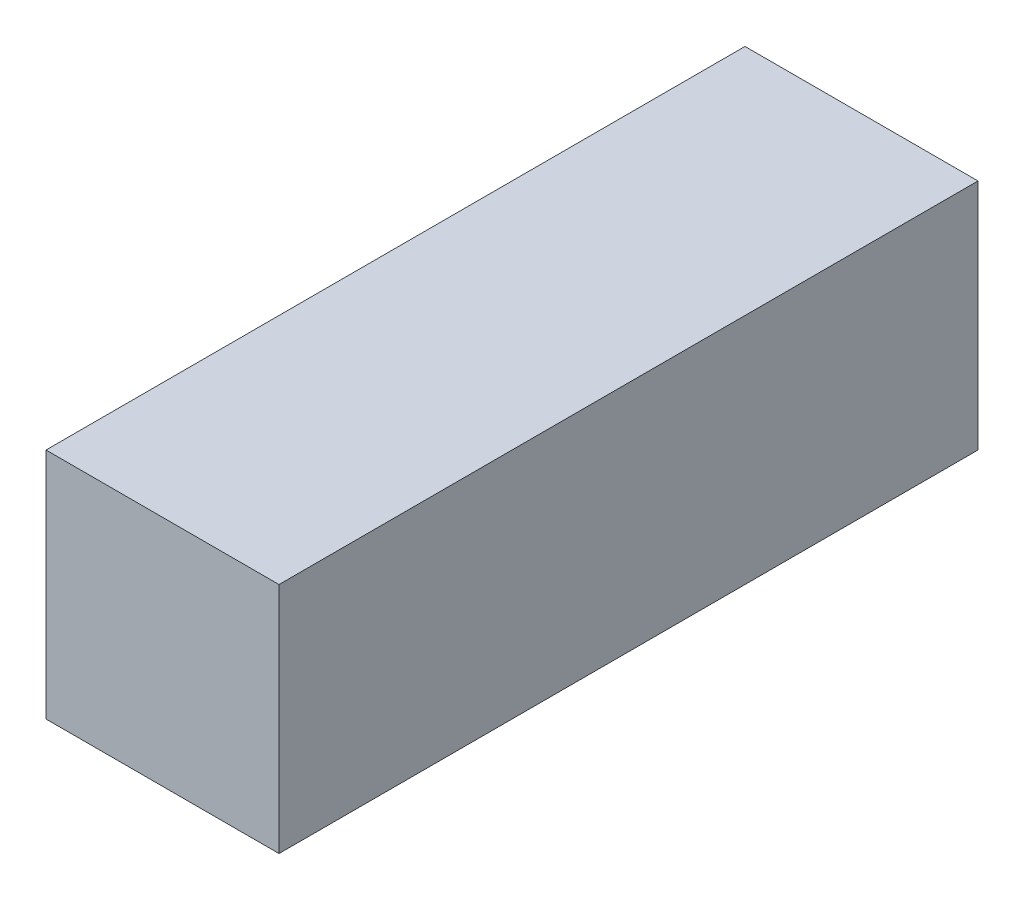
SolidWorks part; units mm, degrees
material "AISI 4340 Steel, annealed"
ref_plane "Front Plane" through (0, 0, 0) normal (0, 0, 1) x (1, 0, 0)
ref_plane "Top Plane" through (0, 0, 0) normal (0, 1, 0) x (1, 0, 0)
ref_plane "Right Plane" through (0, 0, 0) normal (1, 0, 0) x (0, 0, -1)
sketch "Sketch1" plane through (0, 0, 0) normal (0, 0, 1) x (1, 0, 0)
  line L1 (-25, -25) -> (25, -25)
  line L2 (-25, -25) -> (-25, 25)
  line L3 (-25, 25) -> (25, 25)
  line L4 (25, -25) -> (25, 25)
  line L5 (-25, -25) -> (25, 25) construction
  line L6 (-25, 25) -> (25, -25) construction
  point P0 (0, 0)
  dimension "D1" = 50
extrude "Boss-Extrude1" add sketch "Sketch1" against normal blind 150
